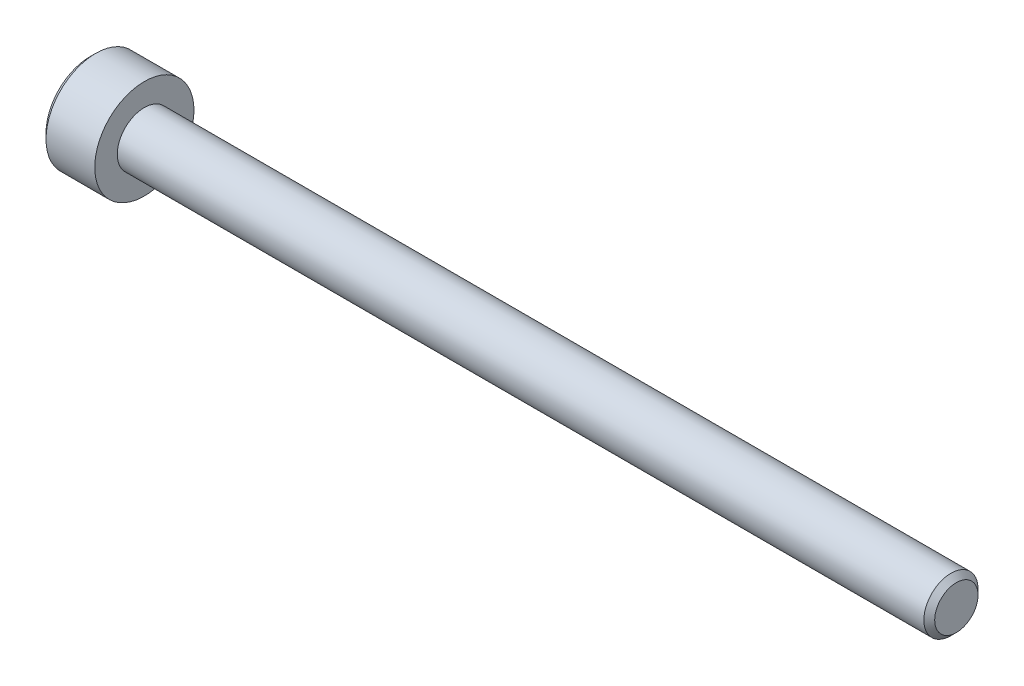
SolidWorks part; units mm, degrees
ref_plane "Front Plane" through (0, 0, 0) normal (0, 0, 1) x (1, 0, 0)
ref_plane "Top Plane" through (0, 0, 0) normal (0, 1, 0) x (1, 0, 0)
ref_plane "Right Plane" through (0, 0, 0) normal (1, 0, 0) x (0, 0, -1)
sketch "Sketch1" plane through (0, 0, 0) normal (0, 0, 1) x (1, 0, 0)
  line L0 (-3, 2.75) -> (-3, 0)
  line L1 (-3, 0) -> (0, 0)
  line L2 (0, 0) -> (0, 2.75)
  line L3 (0, 2.75) -> (-3, 2.75)
  line L4 (-3, 0) -> (0, 0) construction
revolve "Revolve1" add sketch "Sketch1" angle 360 about L4
sketch "Sketch2" plane through (0, 0, 0) normal (1, 0, 0) x (0, 0, -1)
  circle A0 centre (0, 0) radius 1.5
extrude "Boss-Extrude1" add sketch "Sketch2" along normal blind 45
sketch "Sketch3" plane through (-3, 0, 0) normal (-1, 0, 0) x (0, 0, 1)
  line L0 (1.25, -0.7217) -> (1.25, 0.7217)
  line L1 (1.25, 0.7217) -> (0, 1.4434)
  line L2 (0, 1.4434) -> (-1.25, 0.7217)
  line L3 (-1.25, 0.7217) -> (-1.25, -0.7217)
  line L4 (-1.25, -0.7217) -> (0, -1.4434)
  line L5 (0, -1.4434) -> (1.25, -0.7217)
extrude "Cut-Extrude1" cut sketch "Sketch3" against normal blind 1.5
sketch "Sketch4" plane through (0, 0, 0) normal (0, 0, 1) x (1, 0, 0)
  line L0 (-1.5, 1.25) -> (-1.5, 0)
  line L1 (-1.5, 0) -> (-1.1651, 0)
  line L2 (-1.1651, 0) -> (-1.5, 1.25)
  line L3 (-1.5, 0) -> (-1.165, 0) construction
revolve "Cut-Revolve1" cut sketch "Sketch4" angle 360 about L3
chamfer "Chamfer1" distance 0.3 angle 45 2 edges at (45, 0, -1.5) (-3, 0, -2.75)
